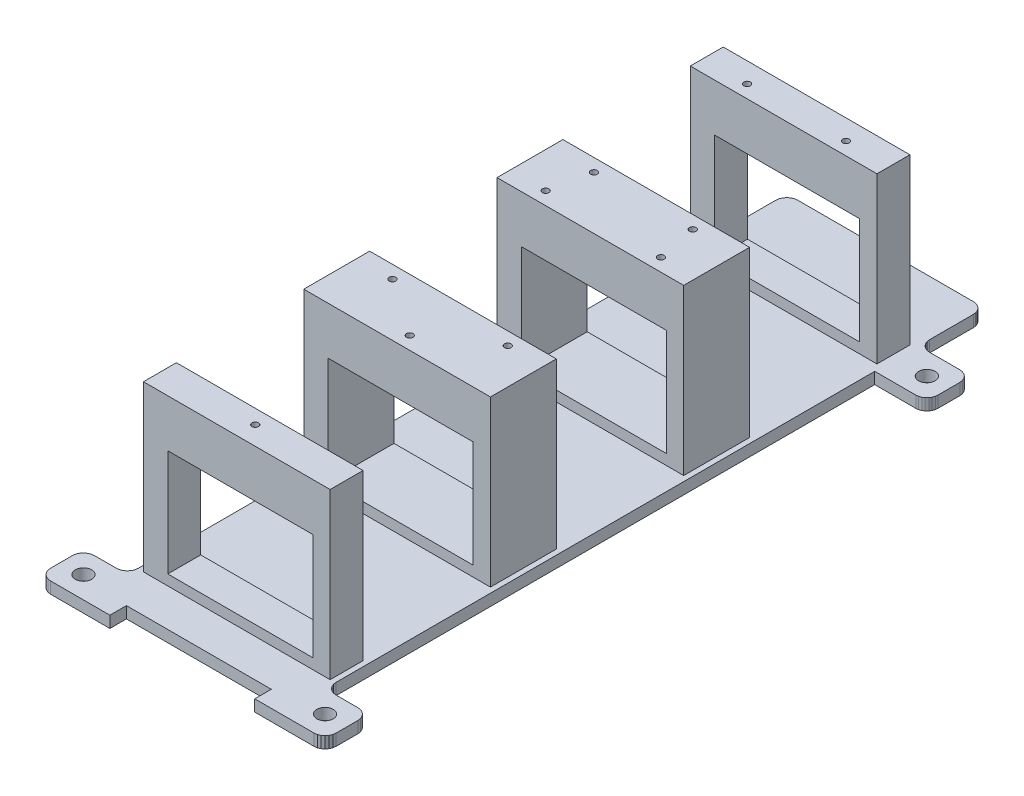
SolidWorks part; units mm, degrees
ref_plane "Front Plane" through (0, 0, 0) normal (0, 0, 1) x (1, 0, 0)
ref_plane "Top Plane" through (0, 0, 0) normal (0, 1, 0) x (1, 0, 0)
ref_plane "Right Plane" through (0, 0, 0) normal (1, 0, 0) x (0, 0, -1)
sketch "Sketch1" plane through (0, 0, 0) normal (0, 1, 0) x (1, 0, 0)
  line L0 (25.5013, 44.0664) -> (18.0013, 44.0664)
  line L1 (18.0013, 44.0664) -> (18.0013, -54.0561)
  line L2 (18.0013, -54.0561) -> (18.0694, -54.5737)
  line L3 (18.0694, -54.5737) -> (18.2692, -55.0561)
  line L4 (18.2692, -55.0561) -> (18.5871, -55.4703)
  line L5 (18.5871, -55.4703) -> (19.0013, -55.7881)
  line L6 (19.0013, -55.7881) -> (19.4837, -55.9879)
  line L7 (19.4837, -55.9879) -> (20.0013, -56.0561)
  line L8 (20.0013, -56.0561) -> (24.0013, -56.0561)
  line L9 (24.0013, -56.0561) -> (24.5176, -56.1237)
  line L10 (24.5176, -56.1237) -> (24.9991, -56.3219)
  line L11 (24.9991, -56.3219) -> (25.4133, -56.6374)
  line L12 (25.4133, -56.6374) -> (25.7323, -57.0489)
  line L13 (25.7323, -57.0489) -> (25.9347, -57.5286)
  line L14 (25.9347, -57.5286) -> (26.0067, -58.0443)
  line L15 (26.0067, -58.0443) -> (26.0067, -62.0473)
  line L16 (26.0067, -62.0473) -> (25.9379, -62.566)
  line L17 (25.9379, -62.566) -> (25.7374, -63.0492)
  line L18 (25.7374, -63.0492) -> (25.4186, -63.4641)
  line L19 (25.4186, -63.4641) -> (25.0034, -63.7824)
  line L20 (25.0034, -63.7824) -> (24.52, -63.9825)
  line L21 (24.52, -63.9825) -> (24.0013, -64.0508)
  line L22 (24.0013, -64.0508) -> (13.1978, -64.0508)
  line L23 (13.1978, -64.0508) -> (13.1978, -61.0346)
  line L24 (13.1978, -61.0346) -> (-13.1883, -61.0346)
  line L25 (-13.1883, -61.0346) -> (-13.1883, -64.049)
  line L26 (-13.1883, -64.049) -> (-23.9987, -64.049)
  line L27 (-23.9987, -64.049) -> (-24.5182, -63.9788)
  line L28 (-24.5182, -63.9788) -> (-25.0019, -63.7769)
  line L29 (-25.0019, -63.7769) -> (-25.417, -63.4569)
  line L30 (-25.417, -63.4569) -> (-25.7355, -63.0405)
  line L31 (-25.7355, -63.0405) -> (-25.9356, -62.5561)
  line L32 (-25.9356, -62.5561) -> (-26.0039, -62.0364)
  line L33 (-26.0039, -62.0364) -> (-26.0039, -58.0537)
  line L34 (-26.0039, -58.0537) -> (-25.9536, -57.6081)
  line L35 (-25.9536, -57.6081) -> (-25.8051, -57.185)
  line L36 (-25.8051, -57.185) -> (-25.566, -56.8056)
  line L37 (-25.566, -56.8056) -> (-25.2484, -56.4892)
  line L38 (-25.2484, -56.4892) -> (-24.8681, -56.2515)
  line L39 (-24.8681, -56.2515) -> (-24.4445, -56.1047)
  line L40 (-24.4445, -56.1047) -> (-23.9987, -56.0561)
  line L41 (-23.9987, -56.0561) -> (-19.9961, -56.0561)
  line L42 (-19.9961, -56.0561) -> (-19.4785, -55.9879)
  line L43 (-19.4785, -55.9879) -> (-18.9961, -55.7881)
  line L44 (-18.9961, -55.7881) -> (-18.5819, -55.4703)
  line L45 (-18.5819, -55.4703) -> (-18.2641, -55.0561)
  line L46 (-18.2641, -55.0561) -> (-18.0643, -54.5737)
  line L47 (-18.0643, -54.5737) -> (-17.9961, -54.0561)
  line L48 (-17.9961, -54.0561) -> (-17.9961, 42.0679)
  line L49 (-17.9961, 42.0679) -> (-18.0643, 42.5856)
  line L50 (-18.0643, 42.5856) -> (-18.2641, 43.0679)
  line L51 (-18.2641, 43.0679) -> (-18.5819, 43.4821)
  line L52 (-18.5819, 43.4821) -> (-18.9961, 43.8)
  line L53 (-18.9961, 43.8) -> (-19.4785, 43.9998)
  line L54 (-19.4785, 43.9998) -> (-19.9961, 44.0679)
  line L55 (-19.9961, 44.0679) -> (-25.4986, 44.0679)
  line L56 (-25.4986, 44.0679) -> (-26.0161, 44.136)
  line L57 (-26.0161, 44.136) -> (-26.4984, 44.3358)
  line L58 (-26.4984, 44.3358) -> (-26.9126, 44.6535)
  line L59 (-26.9126, 44.6535) -> (-27.2305, 45.0675)
  line L60 (-27.2305, 45.0675) -> (-27.4304, 45.5497)
  line L61 (-27.4304, 45.5497) -> (-27.4988, 46.0672)
  line L62 (-27.4988, 46.0672) -> (-27.5006, 50.065)
  line L63 (-27.5006, 50.065) -> (-27.4508, 50.5107)
  line L64 (-27.4508, 50.5107) -> (-27.3029, 50.9342)
  line L65 (-27.3029, 50.9342) -> (-27.0645, 51.3141)
  line L66 (-27.0645, 51.3141) -> (-26.7475, 51.6314)
  line L67 (-26.7475, 51.6314) -> (-26.3677, 51.8701)
  line L68 (-26.3677, 51.8701) -> (-25.9444, 52.0184)
  line L69 (-25.9444, 52.0184) -> (-25.4987, 52.0686)
  line L70 (-25.4987, 52.0686) -> (-19.9961, 52.0686)
  line L71 (-19.9961, 52.0686) -> (-19.4785, 52.1368)
  line L72 (-19.4785, 52.1368) -> (-18.9961, 52.3366)
  line L73 (-18.9961, 52.3366) -> (-18.5819, 52.6544)
  line L74 (-18.5819, 52.6544) -> (-18.2641, 53.0686)
  line L75 (-18.2641, 53.0686) -> (-18.0643, 53.551)
  line L76 (-18.0643, 53.551) -> (-17.9961, 54.0686)
  line L77 (-17.9961, 54.0686) -> (-17.9961, 62.0508)
  line L78 (-17.9961, 62.0508) -> (-17.928, 62.5684)
  line L79 (-17.928, 62.5684) -> (-17.7282, 63.0508)
  line L80 (-17.7282, 63.0508) -> (-17.4103, 63.465)
  line L81 (-17.4103, 63.465) -> (-16.9961, 63.7828)
  line L82 (-16.9961, 63.7828) -> (-16.5138, 63.9826)
  line L83 (-16.5138, 63.9826) -> (-15.9961, 64.0508)
  line L84 (-15.9961, 64.0508) -> (16.0013, 64.0508)
  line L85 (16.0013, 64.0508) -> (16.5189, 63.9826)
  line L86 (16.5189, 63.9826) -> (17.0013, 63.7828)
  line L87 (17.0013, 63.7828) -> (17.4155, 63.465)
  line L88 (17.4155, 63.465) -> (17.7333, 63.0508)
  line L89 (17.7333, 63.0508) -> (17.9331, 62.5684)
  line L90 (17.9331, 62.5684) -> (18.0013, 62.0508)
  line L91 (18.0013, 62.0508) -> (18.0013, 54.0656)
  line L92 (18.0013, 54.0656) -> (18.0694, 53.548)
  line L93 (18.0694, 53.548) -> (18.2692, 53.0656)
  line L94 (18.2692, 53.0656) -> (18.5871, 52.6514)
  line L95 (18.5871, 52.6514) -> (19.0013, 52.3336)
  line L96 (19.0013, 52.3336) -> (19.4837, 52.1338)
  line L97 (19.4837, 52.1338) -> (20.0013, 52.0656)
  line L98 (20.0013, 52.0656) -> (25.5048, 52.0656)
  line L99 (25.5048, 52.0656) -> (26.0216, 51.9964)
  line L100 (26.0216, 51.9964) -> (26.5031, 51.796)
  line L101 (26.5031, 51.796) -> (26.9163, 51.478)
  line L102 (26.9163, 51.478) -> (27.2334, 51.064)
  line L103 (27.2334, 51.064) -> (27.4326, 50.5821)
  line L104 (27.4326, 50.5821) -> (27.5006, 50.0651)
  line L105 (27.5006, 50.0651) -> (27.5006, 46.1008)
  line L106 (27.5006, 46.1008) -> (27.4572, 45.6501)
  line L107 (27.4572, 45.6501) -> (27.3135, 45.2208)
  line L108 (27.3135, 45.2208) -> (27.0769, 44.8349)
  line L109 (27.0769, 44.8349) -> (26.7596, 44.512)
  line L110 (26.7596, 44.512) -> (26.3778, 44.2688)
  line L111 (26.3778, 44.2688) -> (25.9511, 44.1177)
  line L112 (25.9511, 44.1177) -> (25.5013, 44.0664)
extrude "Boss-Extrude1" add sketch "Sketch1" along normal blind 2.1
sketch "Sketch2" plane through (0, 2.1, 0) normal (0, 1, 0) x (1, 0, 0)
  line L24 (-26.0039, -58.0537) -> (-26.0039, -62.0364) construction
  line L25 (-23.9987, -64.049) -> (-13.1883, -64.049) construction
  circle A0 centre (-21.9987, -60.049) radius 1.5
  point P24 (-21.9987, -60.049)
  dimension "D2" = 3
  dimension "D1" = 4.0052
  dimension "D3" = 4
extrude "Cut-Extrude1" cut sketch "Sketch2" against normal through all contours A0
sketch "Sketch3" plane through (0, 2.1, 0) normal (0, 1, 0) x (1, 0, 0)
  line L0 (24.0013, -56.0561) -> (20.0013, -56.0561) construction
  line L1 (26.0067, -62.0473) -> (26.0067, -58.0443) construction
  circle A0 centre (22.0067, -60.0561) radius 1.5
  dimension "D1" = 3
  dimension "D2" = 4
  dimension "D3" = 4
extrude "Cut-Extrude2" cut sketch "Sketch3" against normal through all
sketch "Sketch4" plane through (0, 2.1, 0) normal (0, 1, 0) x (1, 0, 0)
  line L0 (-27.5006, 50.065) -> (-27.4988, 46.0672) construction
  line L1 (-19.9961, 52.0686) -> (-25.4987, 52.0686) construction
  circle A0 centre (-23.4997, 48.0686) radius 1.5
  dimension "D1" = 3
  dimension "D2" = 4
  dimension "D3" = 4
sketch "Sketch5" plane through (0, 2.1, 0) normal (0, 1, 0) x (1, 0, 0)
  line L0 (27.5006, 46.1008) -> (27.5006, 50.0651) construction
  line L1 (18.0013, 44.0664) -> (25.5013, 44.0664) construction
  circle A0 centre (23.5006, 48.0664) radius 1.5
  dimension "D1" = 3
  dimension "D2" = 4
  dimension "D3" = 4
extrude "Cut-Extrude3" cut sketch "Sketch4" against normal through all
extrude "Cut-Extrude4" cut sketch "Sketch5" against normal through all
ref_plane "Plane2" through (0, 2.1, 0) normal (0, 1, 0) x (1, 0, 0)
sketch "Sketch7" plane through (0, 2.1, 0) normal (0, 1, 0) x (1, 0, 0)
  line L0 (-16.9562, 51.4321) -> (17.0438, 51.4321)
  line L2 (-16.9562, 51.4321) -> (-16.9562, 45.4321)
  line L4 (-16.9562, 45.4321) -> (17.0438, 45.4321)
  line L5 (17.0438, 45.4321) -> (17.0438, 51.4321)
  dimension "D1" = 6
  dimension "D2" = 34
extrude "Boss-Extrude2" add sketch "Sketch7" along normal blind 30
sketch "Sketch8" plane through (0, 2.1, 0) normal (0, 1, 0) x (1, 0, 0)
  line L0 (-16.9562, 10.2321) -> (17.0438, 10.2321)
  line L1 (-16.9562, 10.2321) -> (-16.9562, 22.2321)
  line L2 (-16.9562, 22.2321) -> (17.0438, 22.2321)
  line L3 (17.0438, 22.2321) -> (17.0438, 10.2321)
  line L4 (-16.9562, 51.4321) -> (-16.9562, 45.4321) construction
  line L6 (-16.9562, 45.4321) -> (17.0438, 45.4321) construction
  point P6 (0.0438, 45.4321)
  point P7 (0.0438, 22.2321)
  point P10 (0, 0)
  dimension "D1" = 23.2
  dimension "D2" = 12
extrude "Boss-Extrude3" add sketch "Sketch8" along normal blind 30
sketch "Sketch9" plane through (0, 2.1, 0) normal (0, 1, 0) x (1, 0, 0)
  line L0 (-16.9562, -24.9679) -> (17.0438, -24.9679)
  line L1 (-16.9562, -24.9679) -> (-16.9562, -12.9679)
  line L2 (-16.9562, -12.9679) -> (17.0438, -12.9679)
  line L3 (17.0438, -12.9679) -> (17.0438, -24.9679)
  line L4 (-16.9562, 22.2321) -> (-16.9562, 10.2321) construction
  line L9 (-16.9562, 10.2321) -> (17.0438, 10.2321) construction
  point P4 (0.0438, 20.7025)
  point P5 (0.0438, -12.9679)
  point P8 (0.0438, 10.2321)
  point P9 (0, 0)
  point P10 (0, 0)
  point P13 (0, 0)
  point P14 (0, 0)
  dimension "D1" = 23.2
  dimension "D2" = 12
extrude "Boss-Extrude4" add sketch "Sketch9" along normal blind 30
sketch "Sketch10" plane through (0, 2.1, 0) normal (0, 1, 0) x (1, 0, 0)
  line L0 (-16.9562, -48.1679) -> (17.0438, -48.1679)
  line L1 (-16.9562, -48.1679) -> (-16.9562, -54.1679)
  line L2 (-16.9562, -54.1679) -> (17.0438, -54.1679)
  line L3 (17.0438, -54.1679) -> (17.0438, -48.1679)
  line L4 (-16.9562, -24.9679) -> (-16.9562, -12.9679) construction
  line L5 (-16.9562, -24.9679) -> (17.0438, -24.9679) construction
  point P4 (0.0438, -48.1679)
  point P7 (0.0438, -24.9679)
  point P8 (0, 0)
  point P11 (0, 0)
  dimension "D1" = 23.2
  dimension "D2" = 6
extrude "Boss-Extrude5" add sketch "Sketch10" along normal blind 30
ref_plane "Plane3" through (0, 32.1, 0) normal (0, 1, 0) x (1, 0, 0)
sketch "Sketch11" plane through (0, 32.1, 0) normal (0, 1, 0) x (1, 0, 0)
  line L0 (-16.9562, 45.4321) -> (17.0438, 45.4321) construction
  line L1 (-16.9562, 51.4321) -> (-16.9562, 45.4321) construction
  circle A0 centre (-8.9562, 47.7821) radius 0.6
  point P6 (0, 0)
  point P7 (0, 0)
  dimension "D1" = 1.2
  dimension "D2" = 2.35
  dimension "D3" = 8
sketch "Sketch12" plane through (0, 32.1, 0) normal (0, 1, 0) x (1, 0, 0)
  line L0 (-16.9562, 45.4321) -> (17.0438, 45.4321) construction
  line L1 (17.0438, 45.4321) -> (17.0438, 51.4321) construction
  circle A1 centre (9.0438, 47.7821) radius 0.6
  point P9 (0, 0)
  dimension "D1" = 1.2
  dimension "D2" = 2.35
  dimension "D3" = 8
extrude "Cut-Extrude5" cut sketch "Sketch11" against normal blind 10
extrude "Cut-Extrude6" cut sketch "Sketch12" against normal blind 10
ref_plane "Plane4" through (0, 32.1, 0) normal (0, 1, 0) x (1, 0, 0)
sketch "Sketch13" plane through (0, 32.1, 0) normal (0, 1, 0) x (1, 0, 0)
  line L0 (17.0438, 22.2321) -> (-16.9562, 22.2321) construction
  circle A0 centre (-8.9562, 19.8821) radius 0.6
  point P5 (0, 0)
  dimension "D1" = 1.2
  dimension "D2" = 2.35
sketch "Sketch14" plane through (0, 32.1, 0) normal (0, 1, 0) x (1, 0, 0)
  circle A0 centre (9.0438, 19.8821) radius 0.6
  dimension "D1" = 1.2
extrude "Cut-Extrude7" cut sketch "Sketch14" against normal blind 10
extrude "Cut-Extrude8" cut sketch "Sketch13" against normal blind 10 contours A0
sketch "Sketch15" plane through (0, 32.1, 0) normal (0, 1, 0) x (1, 0, 0)
  line L1 (-16.9562, 10.2321) -> (17.0438, 10.2321) construction
  line L2 (-16.9562, 22.2321) -> (-16.9562, 10.2321) construction
  circle A0 centre (-10.4562, 12.5821) radius 0.6
  point P6 (0, 0)
  point P7 (0, 0)
  dimension "D1" = 1.2
  dimension "D2" = 2.35
  dimension "D3" = 6.5
sketch "Sketch16" plane through (0, 32.1, 0) normal (0, 1, 0) x (1, 0, 0)
  line L0 (17.0438, 10.2321) -> (17.0438, 22.2321) construction
  circle A0 centre (10.5438, 12.5821) radius 0.6
  point P5 (0, 0)
  point P6 (0, 0)
  dimension "D1" = 1.2
  dimension "D2" = 6.5
extrude "Cut-Extrude9" cut sketch "Sketch16" against normal blind 10
extrude "Cut-Extrude10" cut sketch "Sketch15" against normal blind 10 contours A0
ref_plane "Plane5" through (0, 32.1, 0) normal (0, 1, 0) x (1, 0, 0)
sketch "Sketch17" plane through (0, 32.1, 0) normal (0, 1, 0) x (1, 0, 0)
  line L0 (17.0438, -12.9679) -> (-16.9562, -12.9679) construction
  circle A0 centre (-10.4562, -15.3179) radius 0.6
  dimension "D1" = 1.2
  dimension "D2" = 2.35
sketch "Sketch18" plane through (0, 32.1, 0) normal (0, 1, 0) x (1, 0, 0)
  circle A0 centre (10.5438, -15.3179) radius 0.6
  point P2 (0, 0)
  point P4 (0, 0)
  point P5 (0, 0)
  dimension "D1" = 1.2
extrude "Cut-Extrude11" cut sketch "Sketch17" against normal blind 10
extrude "Cut-Extrude12" cut sketch "Sketch18" against normal blind 10
sketch "Sketch19" plane through (0, 32.1, 0) normal (0, 1, 0) x (1, 0, 0)
  line L0 (-16.9562, -24.9679) -> (17.0438, -24.9679) construction
  circle A0 centre (0, -22.6179) radius 0.6
  point P4 (0, 0)
  dimension "D1" = 1.2
  dimension "D2" = 2.35
ref_plane "Plane6" through (0, 32.1, 0) normal (0, 1, 0) x (1, 0, 0)
sketch "Sketch20" plane through (0, 32.1, 0) normal (0, 1, 0) x (1, 0, 0)
  line L0 (17.0438, -48.1679) -> (-16.9562, -48.1679) construction
  circle A0 centre (0, -50.7679) radius 0.6
  dimension "D1" = 1.2
  dimension "D2" = 2.6
extrude "Cut-Extrude13" cut sketch "Sketch20" against normal blind 10
extrude "Cut-Extrude14" cut sketch "Sketch19" against normal blind 10 contours A0
sketch "Sketch22" plane through (0, 0, 54.1679) normal (0, 0, 1) x (1, 0, 0)
  line L0 (-12.5272, 23.4299) -> (-12.5272, 3.9932)
  line L1 (-12.5272, 3.9932) -> (13.8915, 3.9932)
  line L2 (13.8915, 3.9932) -> (13.8915, 23.4299)
  line L3 (13.8915, 23.4299) -> (-12.5272, 23.4299)
extrude "Cut-Extrude15" cut sketch "Sketch22" against normal through all both and the other way through all
